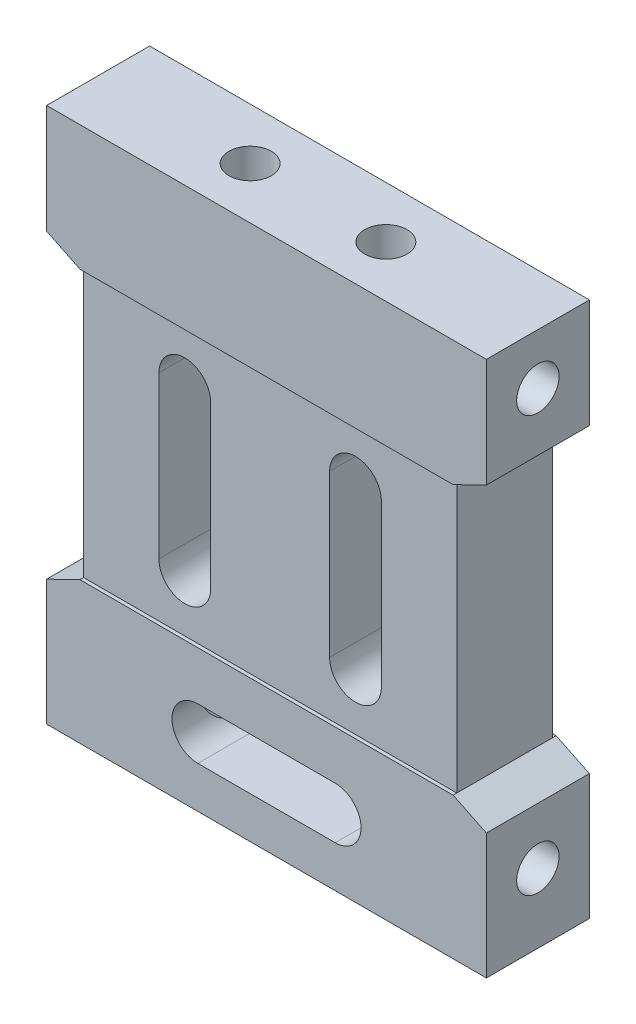
SolidWorks part; units mm, degrees
ref_plane "Piano frontale" through (0, 0, 0) normal (0, 0, 1) x (1, 0, 0)
ref_plane "Piano superiore" through (0, 0, 0) normal (0, 1, 0) x (1, 0, 0)
ref_plane "Piano destro" through (0, 0, 0) normal (1, 0, 0) x (0, 0, -1)
sketch "Schizzo1" plane through (0, 0, 0) normal (0, 0, 1) x (1, 0, 0)
  line L1 (-12.96, -15.79) -> (12.96, -15.79)
  line L2 (-12.96, -15.79) -> (-12.96, 15.79)
  line L3 (-12.96, 15.79) -> (12.96, 15.79)
  line L4 (12.96, -15.79) -> (12.96, 15.79)
  line L5 (-12.96, -15.79) -> (12.96, 15.79) construction
  line L6 (-12.96, 15.79) -> (12.96, -15.79) construction
  point P0 (0, 0)
  dimension "D1" = 25.92
  dimension "D2" = 31.58
extrude "Estrusione-Estrusione1" add sketch "Schizzo1" against normal blind 6.07
sketch "Schizzo2" plane through (0, 0, 0) normal (0, 0, 1) x (1, 0, 0)
  line L0 (0, 15.79) -> (0, -15.79) construction
  line L1 (-12.96, 9.37) -> (-11, 8.415)
  line L2 (-11, 8.415) -> (-11, -7.435)
  line L3 (-11, -7.435) -> (-12.96, -8.39)
  line L4 (12.96, -15.79) -> (12.96, 15.79)
  line L5 (12.96, 15.79) -> (-12.96, 15.79)
  line L6 (-12.96, 15.79) -> (-12.96, -15.79)
  line L7 (-12.96, -15.79) -> (12.96, -15.79)
  line L8 (12.96, -15.79) -> (12.96, 15.79)
  line L9 (12.96, 15.79) -> (-12.96, 15.79)
  line L10 (-12.96, 15.79) -> (-12.96, -15.79)
  line L11 (-12.96, -15.79) -> (12.96, -15.79)
  line L12 (-12.96, 0) -> (12.96, 0) construction
  line L13 (11, -7.435) -> (12.96, -8.39)
  line L14 (11, 8.415) -> (11, -7.435)
  line L15 (12.96, 9.37) -> (11, 8.415)
  line L16 (-5.03, 5.24) -> (-5.03, -4.26) construction
  line L17 (-3.505, 5.24) -> (-3.505, -4.26)
  line L18 (-6.555, 5.24) -> (-6.555, -4.26)
  line L19 (5.03, 5.24) -> (5.03, -4.26) construction
  line L20 (3.505, 5.24) -> (3.505, -4.26)
  line L21 (6.555, 5.24) -> (6.555, -4.26)
  line L22 (-12.96, 15.79) -> (-12.96, -15.79) construction
  line L23 (-11, 0.49) -> (-12.96, -8.39) construction
  line L24 (-11, 0.49) -> (-12.96, 9.37) construction
  line L25 (-11, 0.49) -> (11, 0.49) construction
  line L26 (-4.05, -11.82) -> (4.05, -11.82) construction
  line L27 (-4.05, -10.3) -> (4.05, -10.3)
  line L28 (-4.05, -13.34) -> (4.05, -13.34)
  arc A0 (-3.505, 5.24) -> (-6.555, 5.24) centre (-5.03, 5.24) ccw
  arc A1 (-6.555, -4.26) -> (-3.505, -4.26) centre (-5.03, -4.26) ccw
  arc A2 (3.505, 5.24) -> (6.555, 5.24) centre (5.03, 5.24) cw
  arc A3 (6.555, -4.26) -> (3.505, -4.26) centre (5.03, -4.26) cw
  arc A4 (-4.05, -10.3) -> (-4.05, -13.34) centre (-4.05, -11.82) ccw
  arc A5 (4.05, -13.34) -> (4.05, -10.3) centre (4.05, -11.82) ccw
  point P19 (-5.03, 0.49)
  point P26 (5.03, 0.49)
  point P37 (0, -11.82)
  line M7 (-12.96, 15.79) -> (-12.96, -15.79)
  dimension "D2" = 22
  dimension "D3" = 6.42
  dimension "D4" = 15.85
  dimension "D5" = 3.05
  dimension "D6" = 9.5
  dimension "D7" = 7.01
  dimension "D8" = 7.4
  dimension "D9" = 3.04
  dimension "D10" = 8.1
  dimension "D11" = 2.45
  dimension "D1" = 0
extrude "Taglio-Estrusione1" cut sketch "Schizzo2" against normal through all contours L3 L2 L1 M7 | L18 A1 L17 A0 | A3 L21 A2 L20 | L8 L15 L14 L13 | L28 A5 L27 A4
sketch "Schizzo3" plane through (-12.96, 0, 0) normal (-1, 0, 0) x (0, 0, 1)
  line L0 (-6.07, 8.415) -> (0, 8.415) construction
  line L1 (-6.07, 8.415) -> (-6.07, -7.435) construction
  line L2 (0, 8.415) -> (0, -7.435) construction
  line L3 (-6.07, -7.435) -> (0, -7.435) construction
  line L4 (-6.07, 8.415) -> (0, 8.415)
  line L5 (-6.07, 8.415) -> (-6.07, -7.435)
  line L6 (0, 8.415) -> (0, -7.435)
  line L7 (-6.07, -7.435) -> (0, -7.435)
  line L8 (-3.035, 8.415) -> (-3.035, -7.435) construction
  line L9 (-5.855, 8.415) -> (-5.855, -7.435)
  line L10 (-0.215, 8.415) -> (-0.215, -7.435)
  dimension "D1" = 5.64
extrude "Taglio-Estrusione2" cut sketch "Schizzo3" against normal through all contours L9 L4 L5 L7 | L4 L10 L7 L6
hole_wizard "Foro filettato M3x0.5-1" positions "Schizzo5" profile "Schizzo4" tap size "M3x0.5" standard "Ansi Metric"
sketch "Schizzo5" plane through (0, 15.79, 0) normal (0, 1, 0) x (1, 0, 0)
  line L0 (-12.96, 3.035) -> (12.96, 3.035) construction
  line L1 (-12.96, 6.07) -> (-12.96, 0) construction
  line L2 (12.96, 6.07) -> (12.96, 0) construction
  line L3 (0, 0) -> (0, 6.07) construction
  line L4 (12.96, 0) -> (-12.96, 0) construction
  line L5 (12.96, 6.07) -> (-12.96, 6.07) construction
  point P0 (-4, 3.035)
  point P2 (4, 3.035)
  dimension "D1" = 8
sketch "Schizzo4" plane through (-4, 15.79, -3.035) normal (1, 0, 0) x (0, 0, 1)
  line L0 (0, 0) -> (0, 9.2511)
  line L1 (0, 9.2511) -> (1.25, 8.5)
  line L2 (1.25, 8.5) -> (1.25, 0)
  line L5 (1.25, 0) -> (0, 0)
  line L10 (0, 9.2511) -> (-1.25, 8.5) construction
  line L11 (0, -6.35) -> (0, 107.95) construction
  dimension "Tap Drill Dia." = 2.5
  dimension "Tap Drill Depth" = 8.5
  dimension "Drill Angle" = 118
cosmetic thread "Filettatura del foro1" parameters "D1"=8, "D2"=3
cosmetic thread "Filettatura del foro2" parameters "D1"=8, "D2"=3
hole_wizard "Foro filettato M3x0.5-3" positions "Schizzo9" profile "Schizzo8" tap size "M3x0.5" standard "Ansi Metric"
sketch "Schizzo9" plane through (-12.96, 0, 0) normal (-1, 0, 0) x (0, 0, 1)
  line L0 (-3.035, -11.71) -> (-3.035, 15.79) construction
  line L1 (-6.07, 15.79) -> (0, 15.79) construction
  point P0 (-3.035, 12.79)
  point P2 (-3.035, -11.71)
  dimension "D1" = 24.5
  dimension "D2" = 3
sketch "Schizzo8" plane through (-12.96, 12.79, -3.035) normal (0, 1, 0) x (0, 0, 1)
  line L0 (0, 0) -> (0, 9.2511)
  line L1 (0, 9.2511) -> (1.25, 8.5)
  line L2 (1.25, 8.5) -> (1.25, 0)
  line L5 (1.25, 0) -> (0, 0)
  line L10 (0, 9.2511) -> (-1.25, 8.5) construction
  line L11 (0, -6.35) -> (0, 107.95) construction
  dimension "Tap Drill Dia." = 2.5
  dimension "Tap Drill Depth" = 8.5
  dimension "Drill Angle" = 118
cosmetic thread "Filettatura del foro5" parameters "D1"=8.162, "D2"=3
cosmetic thread "Filettatura del foro6" parameters "D1"=8.5, "D2"=3
mirror "Specchia1" about plane through (0, 0, 0) normal (1, 0, 0) of "Foro filettato M3x0.5-3"
